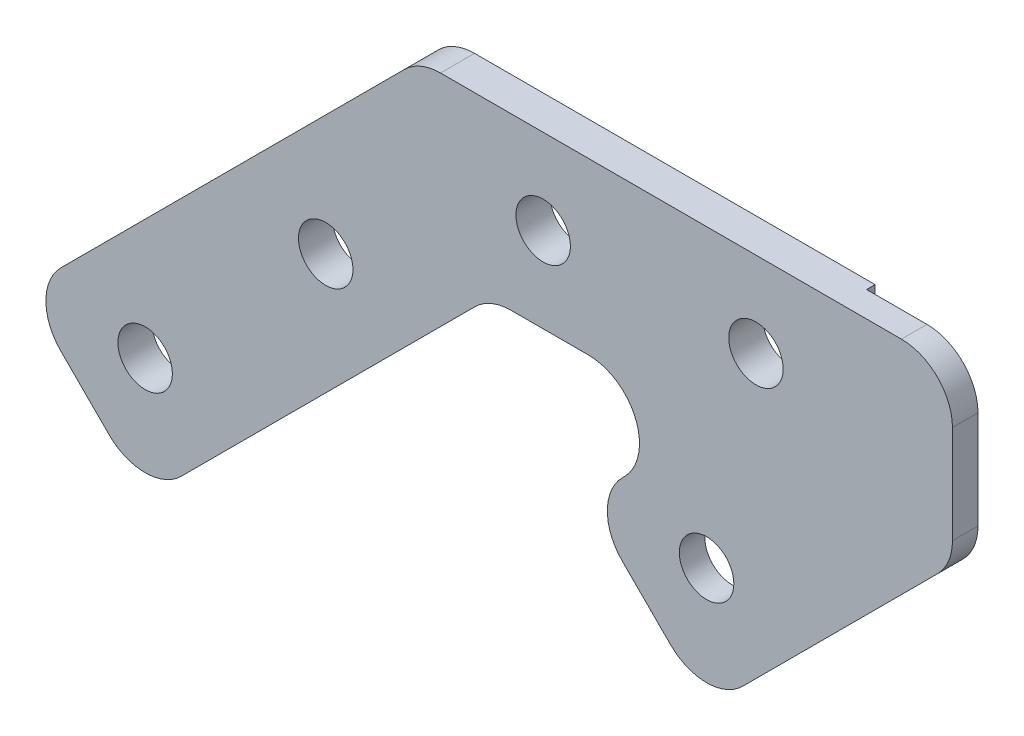
SolidWorks part; units mm, degrees
material "1060 合金"
ref_plane "正面" through (0, 0, 0) normal (0, 0, 1) x (1, 0, 0)
ref_plane "平面" through (0, 0, 0) normal (0, 1, 0) x (1, 0, 0)
ref_plane "右側面" through (0, 0, 0) normal (1, 0, 0) x (0, 0, -1)
sketch "ｽｹｯﾁ1" plane through (0, 0, 0) normal (0, 0, 1) x (1, 0, 0)
  line L0 (-27.3223, -13.1802) -> (-20.2513, -20.2513)
  line L1 (-20.2513, -20.2513) -> (0, 0)
  line L2 (0, 0) -> (20.6289, 0)
  line L3 (20.6289, 0) -> (20.6289, 10)
  line L4 (20.6289, 10) -> (-4.1421, 10)
  line L5 (-4.1421, 10) -> (-27.3223, -13.1802)
  line L6 (20.6289, 5) -> (-9.1421, 5) construction
  line L7 (-23.7868, -16.7157) -> (2.9289, 10) construction
  circle A0 centre (3.1289, 5) radius 1.6
  circle A1 centre (15.6289, 5) radius 1.6
  circle A2 centre (-20.2513, -13.1802) radius 1.6
  circle A3 centre (-9.6447, -2.5736) radius 1.6
  dimension "D7" = 3.2
  dimension "D8" = 17.5
  dimension "D9" = 5
  dimension "D10" = 3.2
  dimension "D11" = 20
  dimension "D12" = 5
  dimension "D1" = 10
  dimension "D2" = 24.7711
  dimension "D3" = 10
  dimension "D4" = 20.2513
  dimension "D5" = 32.7817
  dimension "D6" = 135
extrude "ﾎﾞｽ - 押し出し1" add sketch "ｽｹｯﾁ1" along normal blind 2
sketch "ｽｹｯﾁ3" plane through (0, 0, 2) normal (0, 0, 1) x (1, 0, 0)
  line L0 (5.6563, -7.3726) -> (13.0289, 0)
  line L1 (5.6563, -7.3726) -> (12.7274, -14.4437)
  line L2 (12.7274, -14.4437) -> (27.1711, 0)
  line L3 (27.1711, 0) -> (27.1711, 10)
  line L4 (27.1711, 10) -> (10.6289, 10)
  line L6 (10.6289, 10) -> (10.6289, 0)
  line L7 (10.6289, 0) -> (13.0289, 0)
  circle A0 centre (15.6289, 5) radius 1.6
  circle A1 centre (12.7274, -7.3726) radius 1.6
  circle A3 centre (15.6289, 5) radius 1.6
  line M17 (0, 0) -> (20.6289, 0)
  line M18 (20.6289, 0) -> (20.6289, 10)
  dimension "D3" = 3.2
  dimension "D4" = 3.2
  dimension "D6" = 5
  dimension "D7" = 5
  dimension "D8" = 5
  dimension "D9" = 5
  dimension "D12" = 3.2
  dimension "D1" = 10
  dimension "D2" = 135
  dimension "D5" = 10
  dimension "D10" = 2.4
  dimension "D11" = 10
  dimension "D13" = 10.4264
extrude "ﾎﾞｽ - 押し出し2" add sketch "ｽｹｯﾁ3" against normal blind 1.5 contours L3 L4 L0 L1 L2 A1 M18 M17
fillet "ﾌｨﾚｯﾄ2" radius 3 9 edges at (-20.2513, -20.2513, 1) (-27.3223, -13.1802, 1) (-4.1421, 10, 1) (27.1711, 0, 1.25) (27.1711, 10, 1.25) (12.7274, -14.4437, 1.25) (5.6563, -7.3726, 1.25) (0, 0, 1) (13.0289, 0, 1.25)
